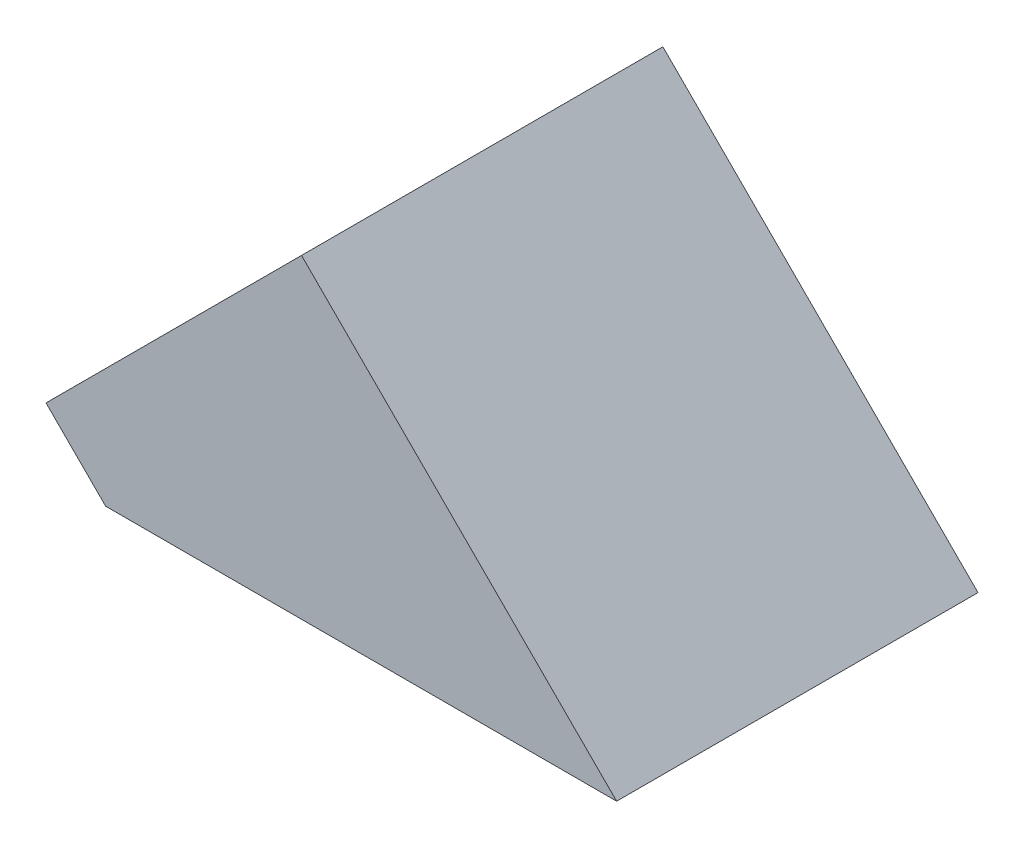
SolidWorks part; units mm, degrees
ref_plane "前视基准面" through (0, 0, 0) normal (0, 0, 1) x (1, 0, 0)
ref_plane "上视基准面" through (0, 0, 0) normal (0, 1, 0) x (1, 0, 0)
ref_plane "右视基准面" through (0, 0, 0) normal (1, 0, 0) x (0, 0, -1)
sketch "草图1" plane through (0, 0, 0) normal (0, 0, 1) x (1, 0, 0)
  line L0 (0, 0) -> (42.4264, 0)
  line L1 (42.4264, 0) -> (16.2635, 26.163)
  line L2 (16.2635, 26.163) -> (-4.9497, 4.9497)
  line L3 (-4.9497, 4.9497) -> (0, 0)
  dimension "D1" = 30
  dimension "D2" = 37
  dimension "D3" = 45
extrude "凸台-拉伸1" add sketch "草图1" along normal blind 30
